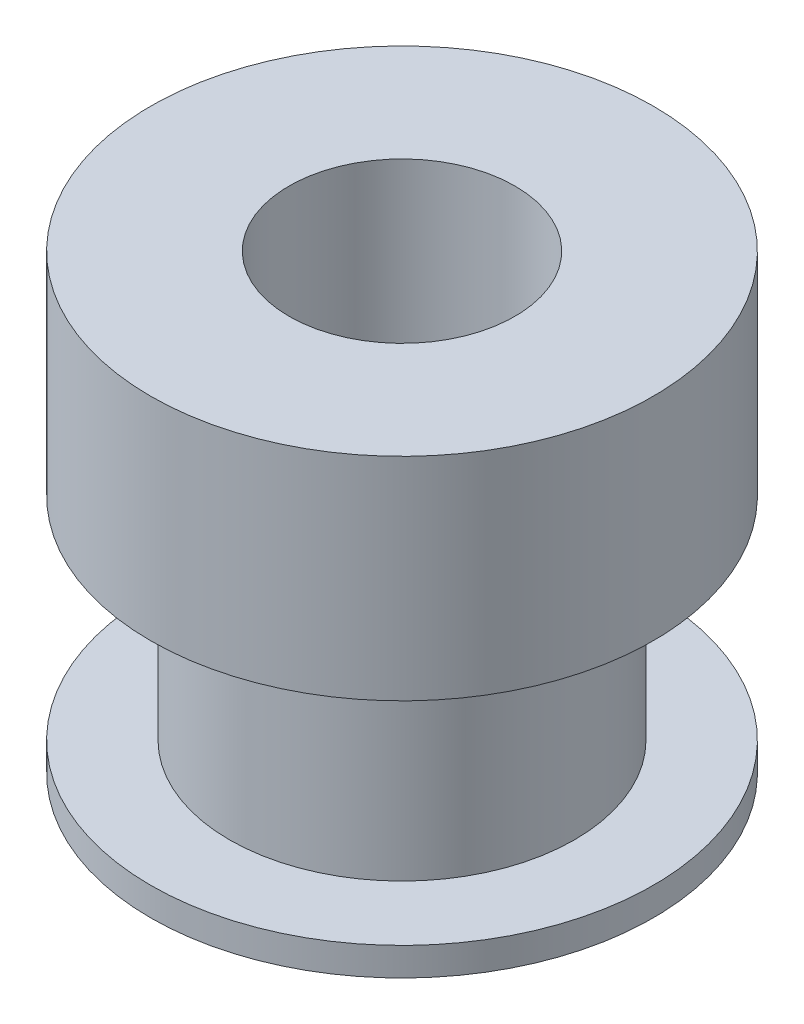
SolidWorks part; units mm, degrees
ref_plane "Face" through (0, 0, 0) normal (0, 0, 1) x (1, 0, 0)
ref_plane "Dessus" through (0, 0, 0) normal (0, 1, 0) x (1, 0, 0)
ref_plane "Droite" through (0, 0, 0) normal (1, 0, 0) x (0, 0, -1)
sketch "Esquisse1" plane through (0, 0, 0) normal (0, 0, 1) x (1, 0, 0)
  line L0 (0, 0) -> (0, 9.7978) construction
  line L1 (4, 0) -> (8.9, 0)
  line L2 (8.9, 0) -> (8.9, 1)
  line L3 (8.9, 1) -> (6.11, 1)
  line L4 (6.11, 1) -> (6.11, 8.5)
  line L5 (6.11, 8.5) -> (8.9, 8.5)
  line L6 (8.9, 8.5) -> (8.9, 16)
  line L9 (8.9, 16) -> (4, 16)
  line L10 (4, 16) -> (4, 0)
  dimension "D1" = 4
  dimension "D2" = 7.5
  dimension "D3" = 8.9
  dimension "D4" = 6.11
  dimension "D5" = 16
  dimension "D6" = 1
revolve "Révolution1" add sketch "Esquisse1" angle 360 about L0
